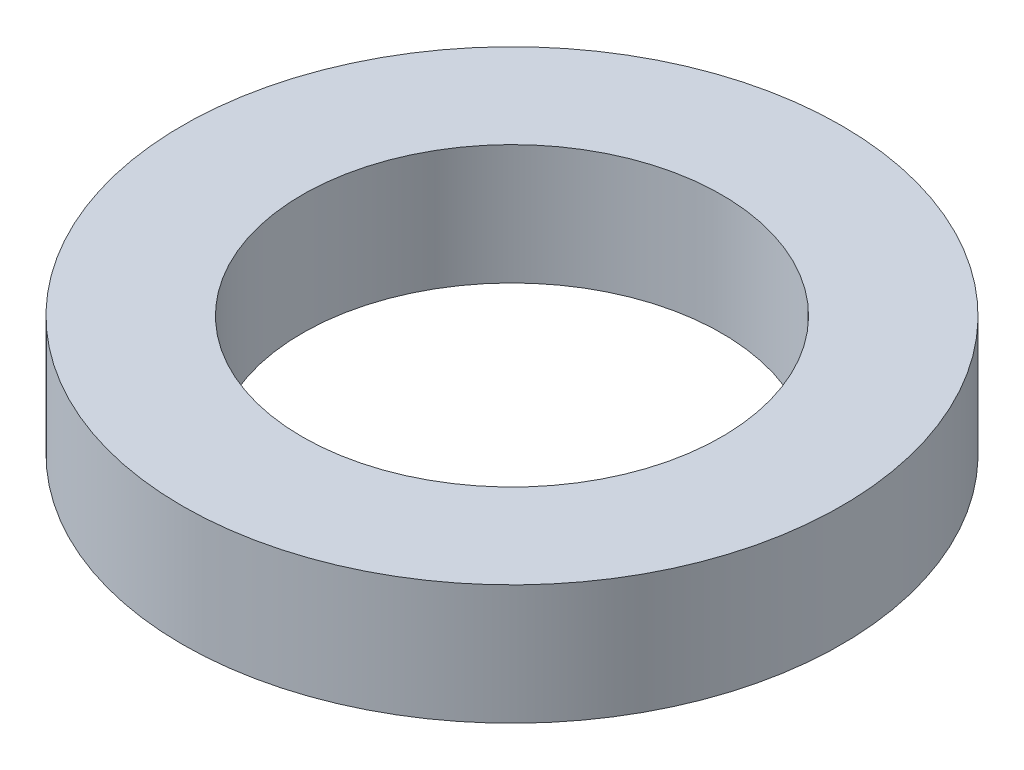
SolidWorks part; units mm, degrees
ref_plane "Alzado" through (0, 0, 0) normal (0, 0, 1) x (1, 0, 0)
ref_plane "Planta" through (0, 0, 0) normal (0, 1, 0) x (1, 0, 0)
ref_plane "Vista lateral" through (0, 0, 0) normal (1, 0, 0) x (0, 0, -1)
sketch "Croquis1" plane through (0, 0, 0) normal (0, 1, 0) x (1, 0, 0)
  circle A0 centre (0, 0) radius 2.75
  circle A1 centre (0, 0) radius 1.75
  dimension "D1" = 5.5
  dimension "D2" = 3.5
extrude "Saliente-Extruir1" add sketch "Croquis1" along normal blind 1
